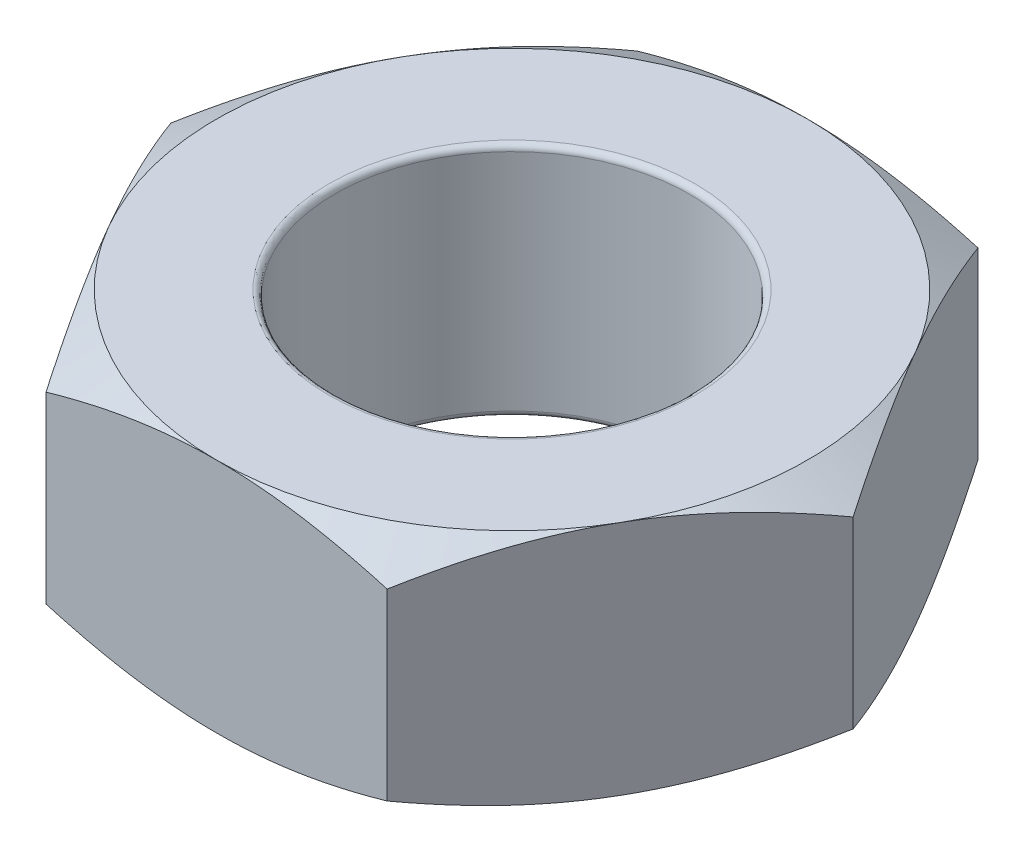
SolidWorks part; units mm, degrees
ref_plane "Front Plane" through (0, 0, 0) normal (0, 0, 1) x (1, 0, 0)
ref_plane "Top Plane" through (0, 0, 0) normal (0, 1, 0) x (1, 0, 0)
ref_plane "Right Plane" through (0, 0, 0) normal (1, 0, 0) x (0, 0, -1)
sketch "Sketch1" plane through (0, 0, 0) normal (0, 1, 0) x (1, 0, 0)
  line L1 (-1.4434, 0) -> (-0.7217, -1.25)
  line L2 (-0.7217, -1.25) -> (0.7217, -1.25)
  line L3 (0.7217, -1.25) -> (1.4434, 0)
  line L4 (1.4434, 0) -> (0.7217, 1.25)
  line L5 (0.7217, 1.25) -> (-0.7217, 1.25)
  line L6 (-0.7217, 1.25) -> (-1.4434, 0)
  circle A0 centre (0, 0) radius 0.75
  circle A1 centre (0, 0) radius 1.25 construction
  dimension "D1" = 1.5
  dimension "D2" = 2.5
extrude "Boss-Extrude3" add sketch "Sketch1" along normal blind 1
sketch "Sketch3" plane through (0, 1, 0) normal (0, 1, 0) x (1, 0, 0)
  circle A0 centre (0, 0) radius 1.25 construction
  circle A1 centre (0, 0) radius 1.25
extrude "Cut-Extrude1" cut sketch "Sketch3" against normal blind 1 draft 60 flip side to cut
sketch "Sketch4" plane through (0, 0, 0) normal (0, -1, 0) x (1, 0, 0)
  circle A1 centre (0, 0) radius 1.25
  circle A2 centre (0, 0) radius 1.25
  dimension "D1" = 0
extrude "Cut-Extrude2" cut sketch "Sketch4" against normal blind 1 draft 60 flip side to cut
fillet "Fillet1" radius 0.025 2 edges at (0, 0, 0.75) (0, 1, 0.75)
